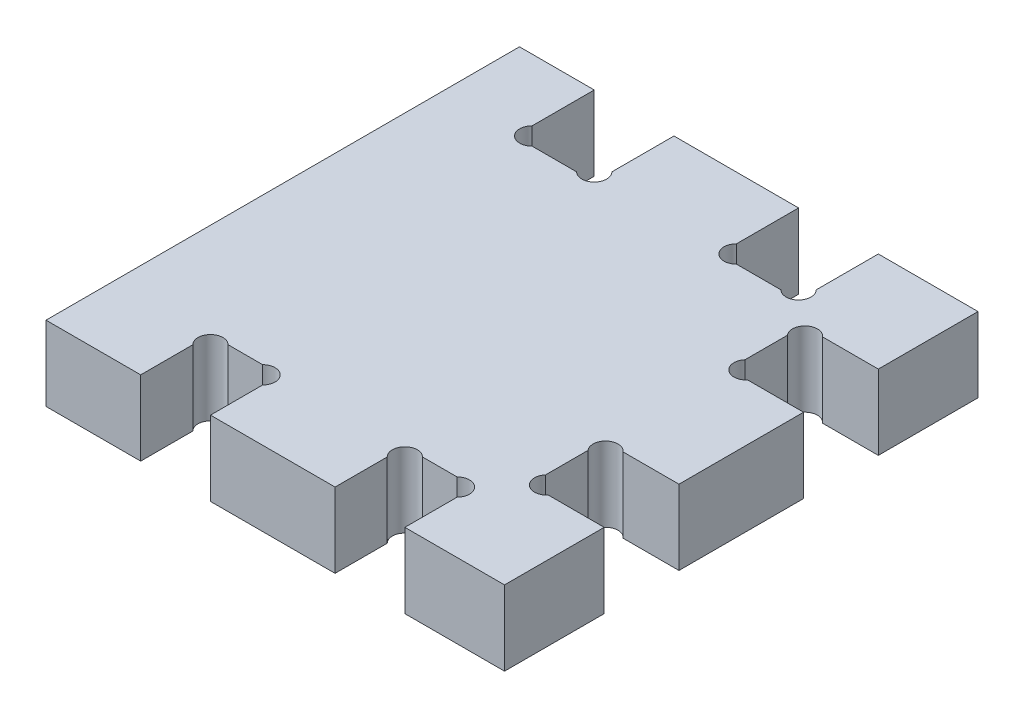
SolidWorks part; units mm, degrees
ref_plane "Front Plane" through (0, 0, 0) normal (0, 0, 1) x (1, 0, 0)
ref_plane "Top Plane" through (0, 0, 0) normal (0, 1, 0) x (1, 0, 0)
ref_plane "Right Plane" through (0, 0, 0) normal (1, 0, 0) x (0, 0, -1)
sketch "Sketch1" plane through (0, 0, 0) normal (0, 1, 0) x (1, 0, 0)
  line L0 (0, 95.25) -> (0, 120.65)
  line L1 (0, 120.65) -> (-25.4, 120.65)
  line L2 (0, 44.45) -> (0, 76.2)
  line L3 (-25.4, 120.65) -> (-25.4, 104.8201)
  line L4 (-19.05, 80.3245) -> (-19.05, 91.1255)
  line L5 (-19.05, 40.3255) -> (-19.05, 29.5245)
  line L6 (-45.72, 120.65) -> (-45.72, 104.8201)
  line L7 (-41.2299, 100.33) -> (-29.8901, 100.33)
  line L8 (-14.2218, 95.25) -> (0, 95.25)
  line L9 (0, 76.2) -> (-14.2218, 76.2)
  line L10 (-14.2218, 44.45) -> (0, 44.45)
  line L11 (0, 25.4) -> (-14.2218, 25.4)
  line L12 (0, 0) -> (0, 25.4)
  line L13 (-41.2299, 100.33) -> (-45.72, 104.8201)
  line L14 (-19.05, 91.1255) -> (-14.2218, 95.25)
  line L15 (-45.72, 120.65) -> (-77.47, 120.65)
  line L16 (-77.47, 120.65) -> (-77.47, 104.8201)
  line L17 (-97.79, 120.65) -> (-97.79, 104.8201)
  line L18 (-93.2999, 100.33) -> (-81.9601, 100.33)
  line L19 (-93.2999, 100.33) -> (-97.79, 104.8201)
  line L20 (-97.79, 120.65) -> (-116.84, 120.65)
  line L21 (-116.84, 120.65) -> (-116.84, 0)
  line L22 (-116.84, 0) -> (-92.71, 0)
  line L23 (-92.71, 0) -> (-92.71, 13.2899)
  line L24 (-92.71, 13.2899) -> (-88.2199, 17.78)
  line L25 (-88.2199, 17.78) -> (-79.4201, 17.78)
  line L26 (-79.4201, 17.78) -> (-74.93, 13.2899)
  line L27 (-74.93, 13.2899) -> (-74.93, 0)
  line L28 (-43.18, 0) -> (-43.18, 13.2899)
  line L29 (-43.18, 13.2899) -> (-38.6899, 17.78)
  line L30 (-38.6899, 17.78) -> (-29.8901, 17.78)
  line L31 (-29.8901, 17.78) -> (-25.4, 13.2899)
  line L32 (-25.4, 13.2899) -> (-25.4, 0)
  line L33 (-74.93, 0) -> (-43.18, 0)
  line L34 (-25.4, 0) -> (0, 0)
  arc A0 (-45.72, 104.8201) -> (-41.2299, 100.33) centre (-43.4749, 102.5751) ccw
  arc A1 (-29.8901, 100.33) -> (-25.4, 104.8201) centre (-27.6451, 102.5751) ccw
  arc A2 (-14.2218, 76.2) -> (-19.05, 80.3245) centre (-16.6359, 78.2622) cw
  arc A3 (-14.2218, 95.25) -> (-19.05, 91.1255) centre (-16.6359, 93.1878) ccw
  arc A4 (-14.2218, 44.45) -> (-19.05, 40.3255) centre (-16.6359, 42.3878) ccw
  arc A5 (-14.2218, 25.4) -> (-19.05, 29.5245) centre (-16.6359, 27.4622) cw
  arc A6 (-97.79, 104.8201) -> (-93.2999, 100.33) centre (-95.5449, 102.5751) ccw
  arc A7 (-81.9601, 100.33) -> (-77.47, 104.8201) centre (-79.7151, 102.5751) ccw
  arc A8 (-88.2199, 17.78) -> (-92.71, 13.2899) centre (-90.4649, 15.5349) ccw
  arc A9 (-79.4201, 17.78) -> (-74.93, 13.2899) centre (-77.1751, 15.5349) cw
  arc A10 (-38.6899, 17.78) -> (-43.18, 13.2899) centre (-40.9349, 15.5349) ccw
  arc A11 (-29.8901, 17.78) -> (-25.4, 13.2899) centre (-27.6451, 15.5349) cw
  point P53 (0, 0)
  point P54 (0, 0)
  point P55 (-16.51, 0)
  point P56 (-97.877, 0)
  point P57 (-25.7927, 0)
  point P58 (0, 0)
  dimension "D3" = 3.175
  dimension "D4" = 3.175
  dimension "D15" = 3.175
  dimension "D26" = 3.175
  dimension "D32" = 3.175
  dimension "D36" = 3.175
  dimension "D1" = 19.05
  dimension "D2" = 19.05
  dimension "D5" = 6.35
  dimension "D6" = 6.35
  dimension "D7" = 6.35
  dimension "D8" = 6.35
  dimension "D9" = 14.9255
  dimension "D10" = 19.05
  dimension "D11" = 31.75
  dimension "D12" = 25.4
  dimension "D13" = 20.32
  dimension "D14" = 20.32
  dimension "D16" = 6.35
  dimension "D17" = 6.35
  dimension "D18" = 135
  dimension "D19" = 20.32
  dimension "D20" = 20.32
  dimension "D21" = 6.35
  dimension "D22" = 6.35
  dimension "D23" = 135
  dimension "D24" = 31.75
  dimension "D25" = 19.05
  dimension "D27" = 6.35
  dimension "D28" = 17.78
  dimension "D29" = 17.78
  dimension "D30" = 135
  dimension "D31" = 31.75
  dimension "D33" = 6.35
  dimension "D34" = 17.78
  dimension "D35" = 135
  dimension "D37" = 25.4
extrude "Boss-Extrude1" add sketch "Sketch1" along normal blind 19.05 contours L30 A11 L32 L34 L12 L11 A5 L5 A4 L10 L2 L9 A2 L4 A3 L8 L0 L1 L3 A1 L7 A0 L6 L15 L16 A7 L18 A6 L17 L20 L21 L22 L23 A8 L25 A9 L27 L33 L28 A10
